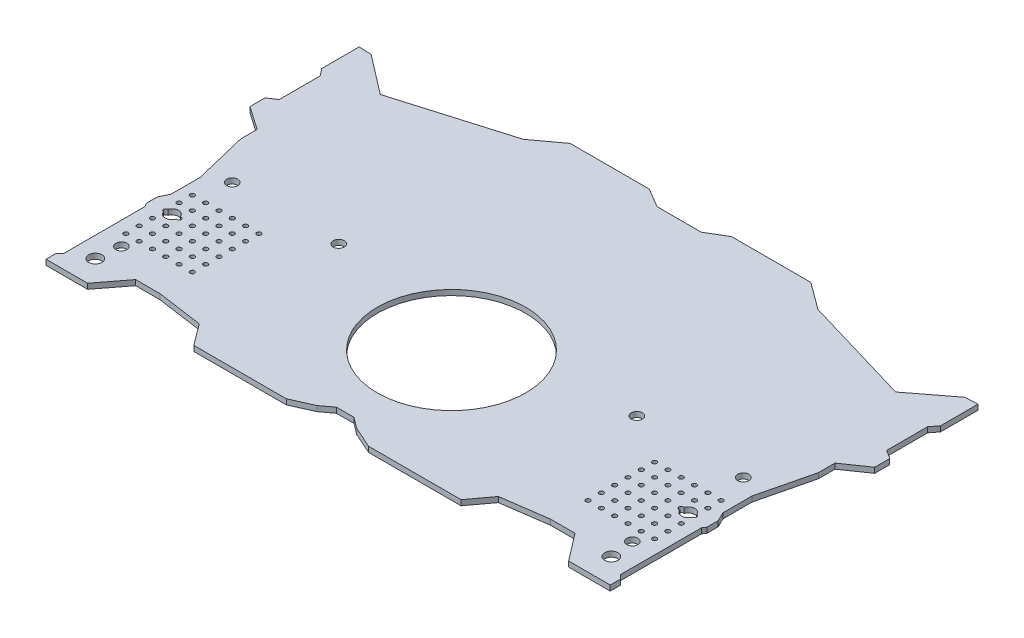
SolidWorks part; units mm, degrees
ref_plane "Alzado" through (0, 0, 0) normal (0, 0, 1) x (1, 0, 0)
ref_plane "Planta" through (0, 0, 0) normal (0, 1, 0) x (1, 0, 0)
ref_plane "Vista lateral" through (0, 0, 0) normal (1, 0, 0) x (0, 0, -1)
sketch "Croquis1" plane through (0, 0, 0) normal (0, 1, 0) x (1, 0, 0)
  line L0 (-7.0473, 41.93) -> (-24.9103, 41.93)
  line L1 (-24.9103, 41.93) -> (-30.9833, 37.451)
  line L2 (-30.9833, 37.451) -> (-55.8703, 30.085)
  line L3 (-55.8703, 30.085) -> (-64.7243, 36.871)
  line L4 (-64.7243, 36.871) -> (-67.5343, 36.997)
  line L5 (-67.5343, 36.997) -> (-67.5343, 28.55)
  line L6 (-67.5343, 28.55) -> (-66.2673, 26.929)
  line L7 (-66.2673, 26.929) -> (-66.2673, 17.685)
  line L8 (-66.2673, 17.685) -> (-68.2053, 16.424)
  line L9 (-68.2053, 16.424) -> (-68.2053, 13.036)
  line L10 (-68.2053, 13.036) -> (-62.9173, 9.371)
  line L11 (-62.9173, 9.371) -> (-62.9173, 5.635)
  line L12 (-62.9173, 5.635) -> (-59.9893, -6.393)
  line L13 (-59.9893, -6.393) -> (-59.9918, -12.9655)
  line L14 (-59.9918, -12.9655) -> (-60.9943, -15.058)
  line L15 (-60.9943, -15.058) -> (-60.9943, -17.609)
  line L16 (-60.9943, -17.609) -> (-60.5083, -18.284)
  line L17 (-60.5083, -18.284) -> (-60.5083, -36.568)
  line L18 (-60.5083, -36.568) -> (-61.3803, -37.498)
  line L19 (-61.3803, -37.498) -> (-61.3803, -39.775)
  line L20 (-61.3803, -39.775) -> (-52.0053, -39.775)
  line L21 (-52.0053, -39.775) -> (-47.3133, -33.645)
  line L22 (-47.3133, -33.645) -> (-41.7873, -33.645)
  line L23 (-41.7873, -33.645) -> (-31.4873, -35.105)
  line L24 (-31.4873, -35.105) -> (-27.9103, -39.931)
  line L25 (-27.9103, -39.931) -> (-7.0473, -39.931)
  line L26 (-7.0473, -39.931) -> (-2.2763, -37.8)
  line L27 (-2.2763, -37.8) -> (0.2637, -35.916)
  line L28 (0.2637, -35.916) -> (4.1907, -35.916)
  line L29 (2.2272, -23.2997) -> (2.2272, -16.2341) construction
  line L30 (-7.0473, 41.93) -> (-2.7713, 39.386)
  line L31 (-2.7713, 39.386) -> (7.2257, 39.386)
  line L32 (11.5017, 41.93) -> (7.2257, 39.386)
  line L33 (6.7307, -37.8) -> (4.1907, -35.916)
  line L34 (11.5017, -39.931) -> (6.7307, -37.8)
  line L35 (32.3647, -39.931) -> (11.5017, -39.931)
  line L36 (35.9417, -35.105) -> (32.3647, -39.931)
  line L37 (46.2417, -33.645) -> (35.9417, -35.105)
  line L38 (51.7677, -33.645) -> (46.2417, -33.645)
  line L39 (56.4597, -39.775) -> (51.7677, -33.645)
  line L40 (65.8347, -39.775) -> (56.4597, -39.775)
  line L41 (65.8347, -37.498) -> (65.8347, -39.775)
  line L42 (64.9627, -36.568) -> (65.8347, -37.498)
  line L43 (64.9627, -18.284) -> (64.9627, -36.568)
  line L44 (65.4487, -17.609) -> (64.9627, -18.284)
  line L45 (65.4487, -15.058) -> (65.4487, -17.609)
  line L46 (64.4462, -12.9655) -> (65.4487, -15.058)
  line L47 (64.4437, -6.393) -> (64.4462, -12.9655)
  line L48 (67.3717, 5.635) -> (64.4437, -6.393)
  line L49 (67.3717, 9.371) -> (67.3717, 5.635)
  line L50 (72.6597, 13.036) -> (67.3717, 9.371)
  line L51 (72.6597, 16.424) -> (72.6597, 13.036)
  line L52 (70.7217, 17.685) -> (72.6597, 16.424)
  line L53 (70.7217, 26.929) -> (70.7217, 17.685)
  line L54 (71.9887, 28.55) -> (70.7217, 26.929)
  line L55 (71.9887, 36.997) -> (71.9887, 28.55)
  line L56 (69.1787, 36.871) -> (71.9887, 36.997)
  line L57 (60.3247, 30.085) -> (69.1787, 36.871)
  line L58 (35.4377, 37.451) -> (60.3247, 30.085)
  line L59 (29.3647, 41.93) -> (35.4377, 37.451)
  line L60 (11.5017, 41.93) -> (29.3647, 41.93)
  circle A0 centre (-31.3823, -3.774) radius 1.25
  circle A1 centre (-55.3823, -3.774) radius 1.25
  circle A2 centre (-55.9783, -16.791) radius 1.5
  circle A3 centre (-55.3823, -28.774) radius 1.25
  circle A4 centre (-55.9493, -34.086) radius 1.5
  circle A5 centre (-42.3813, -25.775) radius 0.5
  circle A6 centre (-45.3813, -25.775) radius 0.5
  circle A7 centre (-48.3813, -25.775) radius 0.5
  circle A8 centre (-51.3813, -25.775) radius 0.5
  circle A9 centre (-54.3813, -25.775) radius 0.5
  circle A10 centre (-57.3813, -25.775) radius 0.5
  circle A11 centre (-42.3813, -22.775) radius 0.5
  circle A12 centre (-45.3813, -22.775) radius 0.5
  circle A13 centre (-48.3813, -22.775) radius 0.5
  circle A14 centre (-51.3813, -22.775) radius 0.5
  circle A15 centre (-54.3813, -22.775) radius 0.5
  circle A16 centre (-57.3813, -22.775) radius 0.5
  circle A17 centre (-42.3813, -19.775) radius 0.5
  circle A18 centre (-45.3813, -19.775) radius 0.5
  circle A19 centre (-48.3813, -19.775) radius 0.5
  circle A20 centre (-51.3813, -19.775) radius 0.5
  circle A21 centre (-54.3813, -19.775) radius 0.5
  circle A22 centre (-57.3813, -19.775) radius 0.5
  circle A23 centre (-42.3813, -16.775) radius 0.5
  circle A24 centre (-45.3813, -16.775) radius 0.5
  circle A25 centre (-48.3813, -16.775) radius 0.5
  circle A26 centre (-51.3813, -16.775) radius 0.5
  circle A27 centre (-54.3813, -16.775) radius 0.5
  circle A28 centre (-57.3813, -16.775) radius 0.5
  circle A29 centre (-42.3813, -13.775) radius 0.5
  circle A30 centre (-45.3813, -13.775) radius 0.5
  circle A31 centre (-48.3813, -13.775) radius 0.5
  circle A32 centre (-51.3813, -13.775) radius 0.5
  circle A33 centre (-54.3813, -13.775) radius 0.5
  circle A34 centre (-57.3813, -13.775) radius 0.5
  circle A35 centre (-42.3813, -10.775) radius 0.5
  circle A36 centre (-45.3813, -10.775) radius 0.5
  circle A37 centre (-48.3813, -10.775) radius 0.5
  circle A38 centre (-51.3813, -10.775) radius 0.5
  circle A39 centre (-54.3813, -10.775) radius 0.5
  circle A40 centre (-57.3813, -10.775) radius 0.5
  circle A52 centre (61.8357, -10.775) radius 0.5
  circle A53 centre (58.8357, -10.775) radius 0.5
  circle A54 centre (55.8357, -10.775) radius 0.5
  circle A55 centre (52.8357, -10.775) radius 0.5
  circle A56 centre (49.8357, -10.775) radius 0.5
  circle A57 centre (46.8357, -10.775) radius 0.5
  circle A58 centre (61.8357, -13.775) radius 0.5
  circle A59 centre (58.8357, -13.775) radius 0.5
  circle A60 centre (55.8357, -13.775) radius 0.5
  circle A61 centre (52.8357, -13.775) radius 0.5
  circle A62 centre (49.8357, -13.775) radius 0.5
  circle A63 centre (46.8357, -13.775) radius 0.5
  circle A64 centre (61.8357, -16.775) radius 0.5
  circle A65 centre (58.8357, -16.775) radius 0.5
  circle A66 centre (55.8357, -16.775) radius 0.5
  circle A67 centre (52.8357, -16.775) radius 0.5
  circle A68 centre (49.8357, -16.775) radius 0.5
  circle A69 centre (46.8357, -16.775) radius 0.5
  circle A70 centre (61.8357, -19.775) radius 0.5
  circle A71 centre (58.8357, -19.775) radius 0.5
  circle A72 centre (55.8357, -19.775) radius 0.5
  circle A73 centre (52.8357, -19.775) radius 0.5
  circle A74 centre (49.8357, -19.775) radius 0.5
  circle A75 centre (46.8357, -19.775) radius 0.5
  circle A76 centre (61.8357, -22.775) radius 0.5
  circle A77 centre (58.8357, -22.775) radius 0.5
  circle A78 centre (55.8357, -22.775) radius 0.5
  circle A79 centre (52.8357, -22.775) radius 0.5
  circle A80 centre (49.8357, -22.775) radius 0.5
  circle A81 centre (46.8357, -22.775) radius 0.5
  circle A82 centre (61.8357, -25.775) radius 0.5
  circle A83 centre (58.8357, -25.775) radius 0.5
  circle A84 centre (55.8357, -25.775) radius 0.5
  circle A85 centre (52.8357, -25.775) radius 0.5
  circle A86 centre (49.8357, -25.775) radius 0.5
  circle A87 centre (46.8357, -25.775) radius 0.5
  circle A88 centre (60.4037, -34.086) radius 1.5
  circle A89 centre (59.8367, -28.774) radius 1.25
  circle A90 centre (60.4327, -16.791) radius 1.5
  circle A91 centre (59.8367, -3.774) radius 1.25
  circle A92 centre (35.8367, -3.774) radius 1.25
  circle A93 centre (2.0707, -11.795) radius 16.7385
  point P221 (2.2272, 39.386)
  point P223 (2.2272, -35.916)
extrude "Saliente-Extruir1" add sketch "Croquis1" along normal blind 1.2 contours L60 L32 L31 L30 L0 L1 L2 L3 L4 L5 L6 L7 L8 L9 L10 L11 L12 L13 L14 L15 L16 L17 L18 L19 L20 L21 L22 L23 L24 L25 L26 L27 L28 L33 L34 L35 L36 L37 L38 L39 L40 L41 L42 L43 L44 L45 L46 L47 L48 L49 L50
